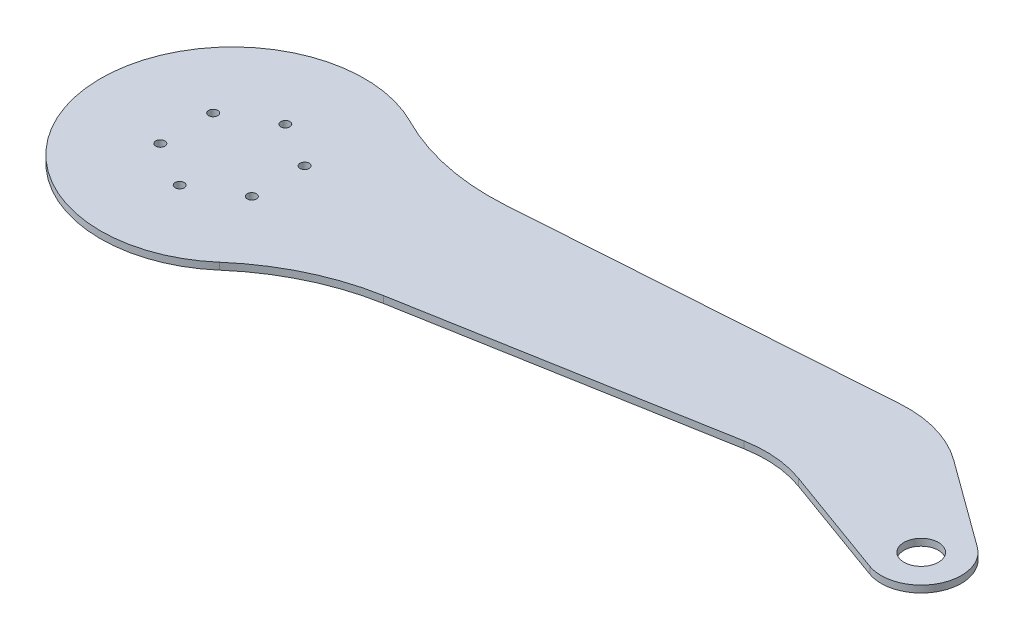
SolidWorks part; units mm, degrees
ref_plane "Front Plane" through (0, 0, 0) normal (0, 0, 1) x (1, 0, 0)
ref_plane "Top Plane" through (0, 0, 0) normal (0, 1, 0) x (1, 0, 0)
ref_plane "Right Plane" through (0, 0, 0) normal (1, 0, 0) x (0, 0, -1)
sketch "Sketch1" plane through (0, 0, 0) normal (0, 1, 0) x (1, 0, 0)
  line L0 (0, 0) -> (300, 0) construction
  line L1 (0, 0) -> (0, 35) construction
  line L2 (-2.3785, 34.9191) -> (6.125, -34.4599) construction
  line L3 (310.3118, 14.1392) -> (294.0372, -16.4528) construction
  line L4 (300, 0) -> (300, 17.5) construction
  line L5 (-2.3785, 34.9191) -> (644.2586, 78.9638)
  line L6 (644.2586, 78.9638) -> (6.125, -34.4599)
  line L7 (294.0372, -16.4528) -> (232.6345, 5.8005)
  line L8 (310.3118, 14.1392) -> (257.5435, 52.6233)
  line L9 (257.5435, 52.6233) -> (232.6345, 5.8005) construction
  line L13 (0, 0) -> (644.2586, 78.9638) construction
  circle A0 centre (0, 0) radius 35 construction
  circle A2 centre (300, 0) radius 17.5
  circle A3 centre (0, 0) radius 23 construction
  circle A4 centre (0, 23) radius 2
  circle A5 centre (19.9186, 11.5) radius 2
  circle A6 centre (19.9186, -11.5) radius 2
  circle A7 centre (0, -23) radius 2
  circle A8 centre (-19.9186, -11.5) radius 2
  circle A9 centre (-19.9186, 11.5) radius 2
  circle A12 centre (300, 0) radius 7.5
  circle A13 centre (0, 0) radius 57.5
  point P11 (304.2835, 18.5356)
  point P31 (0, 0)
  dimension "D2" = 115
  dimension "D4" = 35
  dimension "D7" = 46
  dimension "D8" = 4
  dimension "D12" = 15
  dimension "D10" = 70
  dimension "D1" = 300
  dimension "D5" = 150
  dimension "D6" = 140
  dimension "D9" = 6
extrude "Boss-Extrude2" add sketch "Sketch1" along normal blind 3
fillet "Fillet1" radius 50 2 edges at (232.6345, 1.5, -5.8005) (257.5435, 1.5, -52.6233)
fillet "Fillet2" radius 100 2 edges at (51.0417, 1.5, 26.4763) (43.1368, 1.5, -38.0193)
sketch "Sketch2" plane through (0, 3, 0) normal (0, 1, 0) x (1, 0, 0)
  line L1 (342.132, 1.0293) -> (130, 213.1614)
  line L2 (130, 213.1614) -> (-82.132, 1.0293)
  line L3 (-82.132, 1.0293) -> (130, -211.1027)
  line L4 (130, -211.1027) -> (342.132, 1.0293)
  circle A0 centre (130, 1.0293) radius 150 construction
  dimension "D1" = 300
